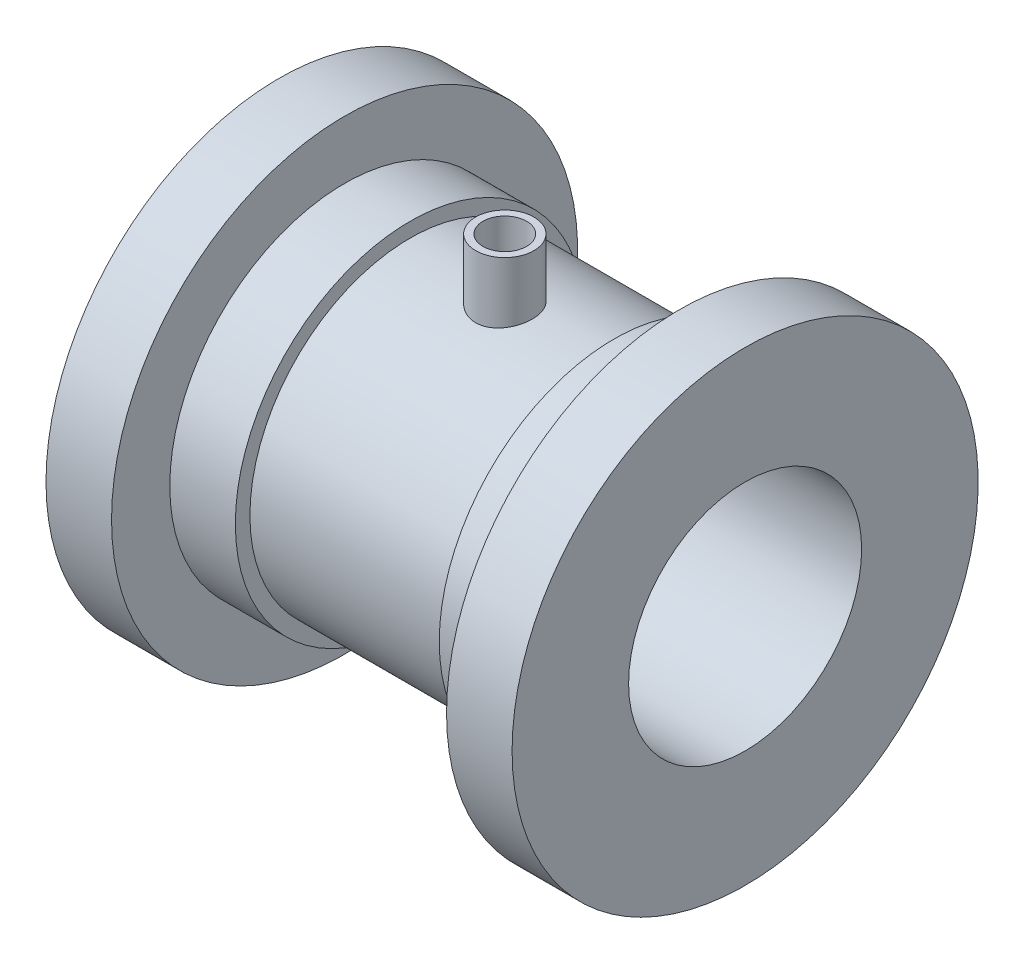
SolidWorks part; units mm, degrees
ref_plane "Front Plane" through (0, 0, 0) normal (0, 0, 1) x (1, 0, 0)
ref_plane "Top Plane" through (0, 0, 0) normal (0, 1, 0) x (1, 0, 0)
ref_plane "Right Plane" through (0, 0, 0) normal (1, 0, 0) x (0, 0, -1)
sketch "Sketch1" plane through (0, 0, 0) normal (0, 0, 1) x (1, 0, 0)
  line L0 (0, 0) -> (64, 0) construction
  line L1 (0, 16) -> (64, 16)
  line L2 (0, 16) -> (0, 32)
  line L3 (0, 32) -> (9, 32)
  line L4 (9, 32) -> (9, 24)
  line L5 (9, 24) -> (18, 24)
  line L6 (18, 24) -> (18, 22)
  line L7 (18, 22) -> (46, 22)
  line L8 (32, 0) -> (32, 8.8092) construction
  line L9 (46, 24) -> (46, 22)
  line L10 (55, 24) -> (46, 24)
  line L11 (55, 32) -> (55, 24)
  line L12 (64, 32) -> (55, 32)
  line L13 (64, 16) -> (64, 32)
  point P5 (32, 0)
  point P15 (32, 22)
  dimension "D1" = 32
  dimension "D2" = 64
  dimension "D3" = 48
  dimension "D4" = 64
  dimension "D5" = 9
  dimension "D6" = 14
  dimension "D7" = 44
revolve "Revolve1" add sketch "Sketch1" angle 360 about L0
ref_plane "Plane1" through (0, 30, 0) normal (0, 1, 0) x (1, 0, 0)
sketch "Sketch2" plane through (0, 30, 0) normal (0, 1, 0) x (1, 0, 0)
  line L0 (18, 22) -> (46, 22) construction
  line L1 (46, 22) -> (18, 22) construction
  line L2 (46, 24) -> (46, -24) construction
  line L3 (46, 22) -> (46, -24) construction
  circle A0 centre (32, -1) radius 4
  point P7 (46, -1)
  point P10 (32, 22)
  dimension "D1" = 8
extrude "Boss-Extrude1" add sketch "Sketch2" against normal up to next
sketch "Sketch3" plane through (0, 30, 0) normal (0, 1, 0) x (1, 0, 0)
  circle A0 centre (32, -1) radius 3
  dimension "D1" = 6
extrude "Cut-Extrude1" cut sketch "Sketch3" against normal through all
